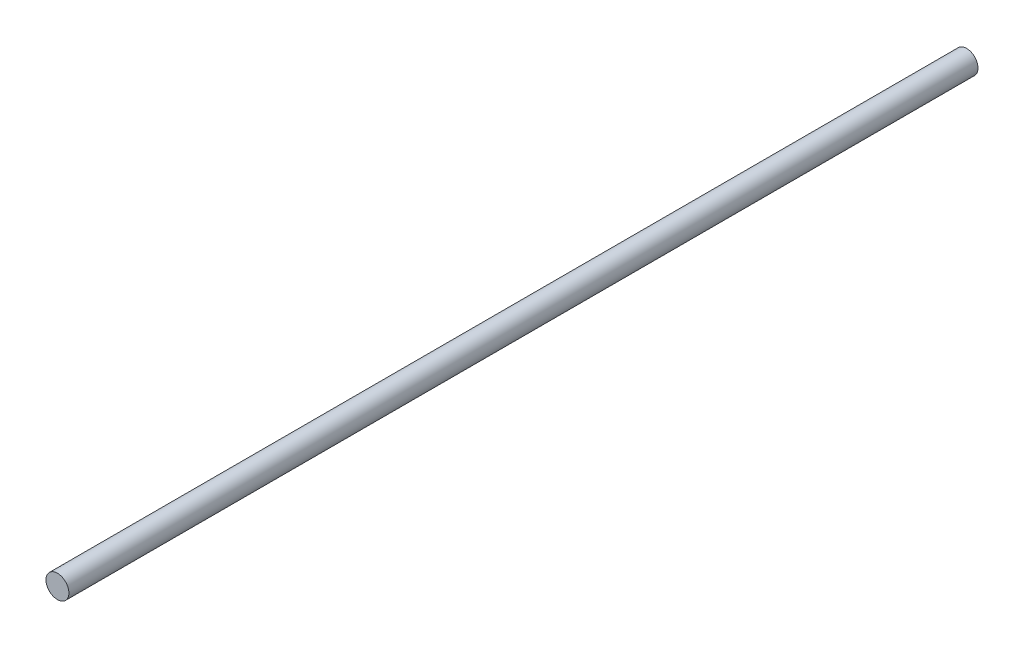
SolidWorks part; units mm, degrees
ref_plane "Front Plane" through (0, 0, 0) normal (0, 0, 1) x (1, 0, 0)
ref_plane "Top Plane" through (0, 0, 0) normal (0, 1, 0) x (1, 0, 0)
ref_plane "Right Plane" through (0, 0, 0) normal (1, 0, 0) x (0, 0, -1)
sketch "Sketch1" plane through (0, 0, 0) normal (0, 0, 1) x (1, 0, 0)
  circle A0 centre (0, 0) radius 2.975
  dimension "D1" = 5.95
extrude "Boss-Extrude1" add sketch "Sketch1" along normal blind 236.22
